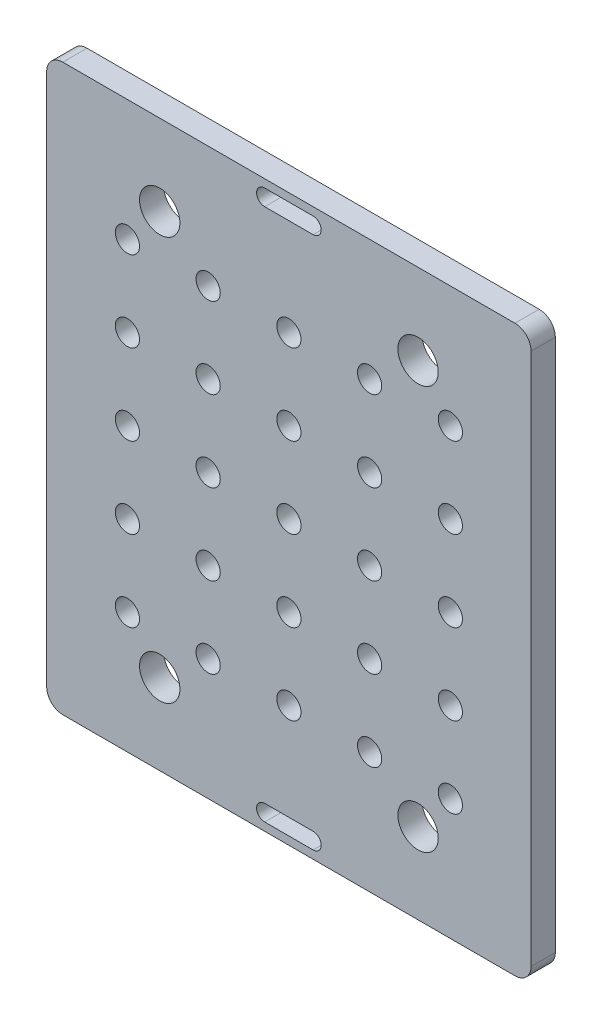
SolidWorks part; units mm, degrees
ref_plane "Front Plane" through (0, 0, 0) normal (0, 0, 1) x (1, 0, 0)
ref_plane "Top Plane" through (0, 0, 0) normal (0, 1, 0) x (1, 0, 0)
ref_plane "Right Plane" through (0, 0, 0) normal (1, 0, 0) x (0, 0, -1)
sketch "Model" plane through (0, 0, 0) normal (0, 0, 1) x (1, 0, 0)
  line L0 (-27, 1) -> (-33, 1)
  line L1 (-33, 3) -> (-27, 3)
  line L2 (-33, 68.9998) -> (-27, 68.9998)
  line L3 (-27, 66.9998) -> (-33, 66.9998)
  line L4 (-2, 70) -> (-58, 70)
  line L5 (-60, 68) -> (-60, 2)
  line L6 (-58, 0) -> (-2, 0)
  line L7 (0, 2) -> (0, 68)
  circle A0 centre (-20, 45) radius 1.5
  circle A1 centre (-10, 35) radius 1.5
  circle A2 centre (-50, 45) radius 1.5
  circle A3 centre (-20, 15) radius 1.5
  circle A4 centre (-20, 35) radius 1.5
  circle A5 centre (-40, 25) radius 1.5
  circle A6 centre (-40, 15) radius 1.5
  circle A7 centre (-30, 25) radius 1.5
  circle A8 centre (-40, 55) radius 1.5
  circle A9 centre (-10, 25) radius 1.5
  circle A10 centre (-30, 45) radius 1.5
  circle A11 centre (-10, 55) radius 1.5
  circle A12 centre (-10, 45) radius 1.5
  circle A13 centre (-50, 15) radius 1.5
  circle A14 centre (-10, 15) radius 1.5
  circle A15 centre (-50, 35) radius 1.5
  circle A16 centre (-40, 45) radius 1.5
  circle A17 centre (-30, 15) radius 1.5
  circle A18 centre (-30, 35) radius 1.5
  circle A19 centre (-40, 35) radius 1.5
  circle A20 centre (-20, 25) radius 1.5
  circle A21 centre (-50, 25) radius 1.5
  circle A22 centre (-50, 55) radius 1.5
  circle A23 centre (-30, 55) radius 1.5
  circle A24 centre (-20, 55) radius 1.5
  circle A25 centre (-46, 60) radius 2.5
  circle A26 centre (-14, 10) radius 2.5
  circle A27 centre (-14, 60) radius 2.5
  circle A28 centre (-46, 10) radius 2.5
  arc A29 (-27, 1) -> (-27, 3) centre (-27, 2) ccw
  arc A30 (-33, 3) -> (-33, 1) centre (-33, 2) ccw
  arc A31 (-33, 68.9998) -> (-33, 66.9998) centre (-33, 67.9998) ccw
  arc A32 (-27, 66.9998) -> (-27, 68.9998) centre (-27, 67.9998) ccw
  arc A33 (0, 68) -> (-2, 70) centre (-2, 68) ccw
  arc A34 (-58, 70) -> (-60, 68) centre (-58, 68) ccw
  arc A35 (-60, 2) -> (-58, 0) centre (-58, 2) ccw
  arc A36 (-2, 0) -> (0, 2) centre (-2, 2) ccw
extrude "Boss-Extrude1" add sketch "Model" along normal blind 3
